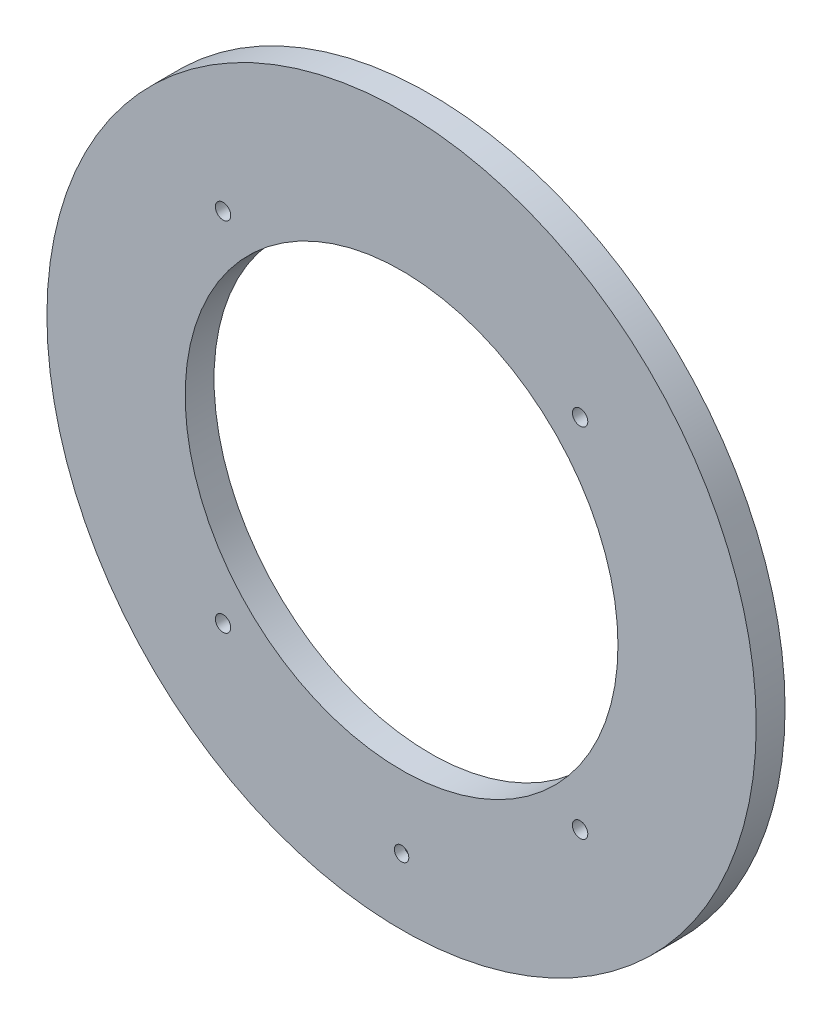
SolidWorks part; units mm, degrees
ref_plane "Piano frontale" through (0, 0, 0) normal (0, 0, 1) x (1, 0, 0)
ref_plane "Piano superiore" through (0, 0, 0) normal (0, 1, 0) x (1, 0, 0)
ref_plane "Piano destro" through (0, 0, 0) normal (1, 0, 0) x (0, 0, -1)
sketch "Schizzo1" plane through (0, 0, 0) normal (0, 0, 1) x (1, 0, 0)
  circle A0 centre (0, 0) radius 147.5
  circle A1 centre (0, 0) radius 90
  dimension "D1" = 295
  dimension "D2" = 180
extrude "Estrusione-Estrusione1" add sketch "Schizzo1" along normal blind 12 contours A0 A1
sketch "Schizzo3" plane through (0, 0, 0) normal (0, 0, -1) x (-1, 0, 0)
  arc A0 (83.5624, 99.5858) -> (70.7066, 84.2649) centre (77.1345, 91.9253) ccw
  arc A1 (-98.9117, -48.1298) -> (-116.8956, -56.8807) centre (-107.9037, -52.5052) ccw
  arc A2 (-98.9117, -48.1298) -> (70.7066, 84.2649) centre (0, 0) ccw
  arc A3 (-116.8956, -56.8807) -> (83.5624, 99.5858) centre (0, 0) ccw
  dimension "D1" = 20
  dimension "D2" = 20
  dimension "D5" = 120
extrude "Taglio-Estrusione1" cut sketch "Schizzo3" against normal blind 8
sketch "Schizzo10" plane through (0, 0, 8) normal (0, 0, -1) x (-1, 0, 0)
  line L0 (0, 0) -> (0, -120)
  circle A0 centre (0, -120) radius 3
extrude "Taglio-Estrusione2" cut sketch "Schizzo10" against normal up to surface (4 mm away) contours A0 up to face at (90, 0, 12)
hole_wizard "Foro per Vite M6-1" positions "Schizzo12" profile "Schizzo13" hole size "M6" standard "ISO"
sketch "Schizzo12" plane through (0, 0, 12) normal (0, 0, 1) x (1, 0, 0)
  line L0 (0, 0) -> (-74.2462, -74.2462) construction
  point P0 (-74.2462, -74.2462)
  dimension "D2" = 105
sketch "Schizzo13" plane through (-74.2462, -74.2462, 12) normal (1, 0, 0) x (0, -1, 0)
  line L0 (0, 0) -> (0, 7.9228)
  line L1 (0, 7.9228) -> (3.2, 6)
  line L2 (3.2, 6) -> (3.2, 0)
  line L5 (3.2, 0) -> (0, 0)
  line L10 (0, 7.9228) -> (-3.2, 6) construction
  line L11 (0, -6.35) -> (0, 107.95) construction
  dimension "Hole Dia." = 6.4
  dimension "Hole Depth" = 6
  dimension "Drill Angle" = 118
pattern_circular "RipetizioneCircolare3" count 4 over 360 about axis through (0, 0, 0) along (0, 0, 1) of "Foro per Vite M6-1"
